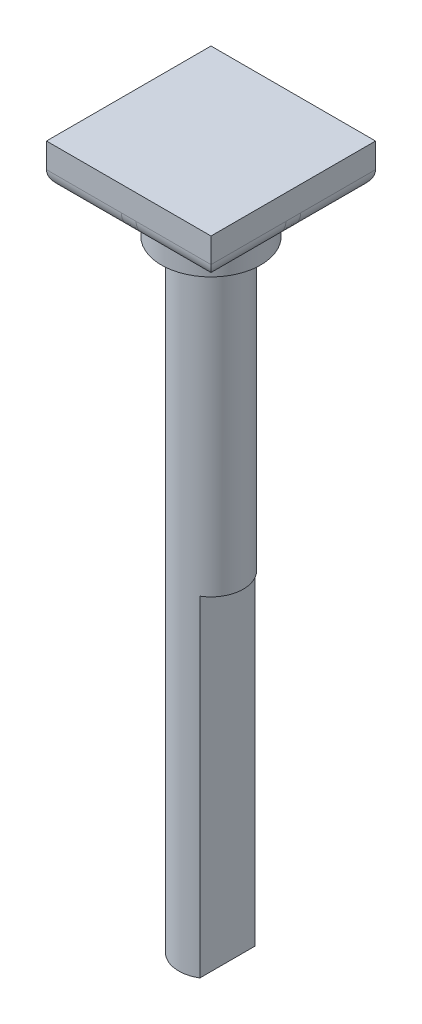
SolidWorks part; units mm, degrees
ref_plane "Alzado" through (0, 0, 0) normal (0, 0, 1) x (1, 0, 0)
ref_plane "Planta" through (0, 0, 0) normal (0, 1, 0) x (1, 0, 0)
ref_plane "Vista lateral" through (0, 0, 0) normal (1, 0, 0) x (0, 0, -1)
sketch "Croquis1" plane through (0, 0, 0) normal (1, 0, 0) x (0, 0, -1)
  line L0 (0, 0) -> (0, 19394.6636) construction
  line L1 (0, 0) -> (-3.9, 0)
  line L2 (-3.9, 0) -> (-3.9, 75)
  line L3 (-3.9, 75) -> (-6, 75)
  line L4 (-6, 75) -> (-6, 80)
  line L5 (-6, 80) -> (0, 80)
  line L6 (0, 80) -> (0, 0)
  dimension "D1" = 75
  dimension "D2" = 5
  dimension "D3" = 6
  dimension "D4" = 3.9
revolve "Revolución1" add sketch "Croquis1" angle 360 about L0
sketch "Croquis2" plane through (0, 80, 0) normal (0, 1, 0) x (1, 0, 0)
  line L5 (-9.95, -9.95) -> (9.95, -9.95)
  line L6 (-9.95, -9.95) -> (-9.95, 9.95)
  line L7 (-9.95, 9.95) -> (9.95, 9.95)
  line L8 (9.95, -9.95) -> (9.95, 9.95)
  line L9 (-9.95, -9.95) -> (9.95, 9.95) construction
  line L10 (-9.95, 9.95) -> (9.95, -9.95) construction
  point P0 (0, 0)
  dimension "D1" = 19.9
extrude "Saliente-Extruir1" add sketch "Croquis2" along normal blind 5 contours L5 L8 L7 L6
sketch "Croquis3" plane through (0, 0, 0) normal (0, -1, 0) x (1, 0, 0)
  line L0 (2, 3.3481) -> (2, -3.3481)
  line L1 (0, 0) -> (2, 0) construction
  circle A0 centre (0, 0) radius 3.9 construction
  dimension "D1" = 2
extrude "Cortar-Extruir1" cut sketch "Croquis3" against normal blind 40 and the other way through all
fillet "Redondeo3" radius 2 1 edges at (0, 80, -6)
fillet "Redondeo4" radius 2 4 edges at (0, 80, 9.95) (9.95, 80, 0) (0, 80, -9.95) (-9.95, 80, 0)
